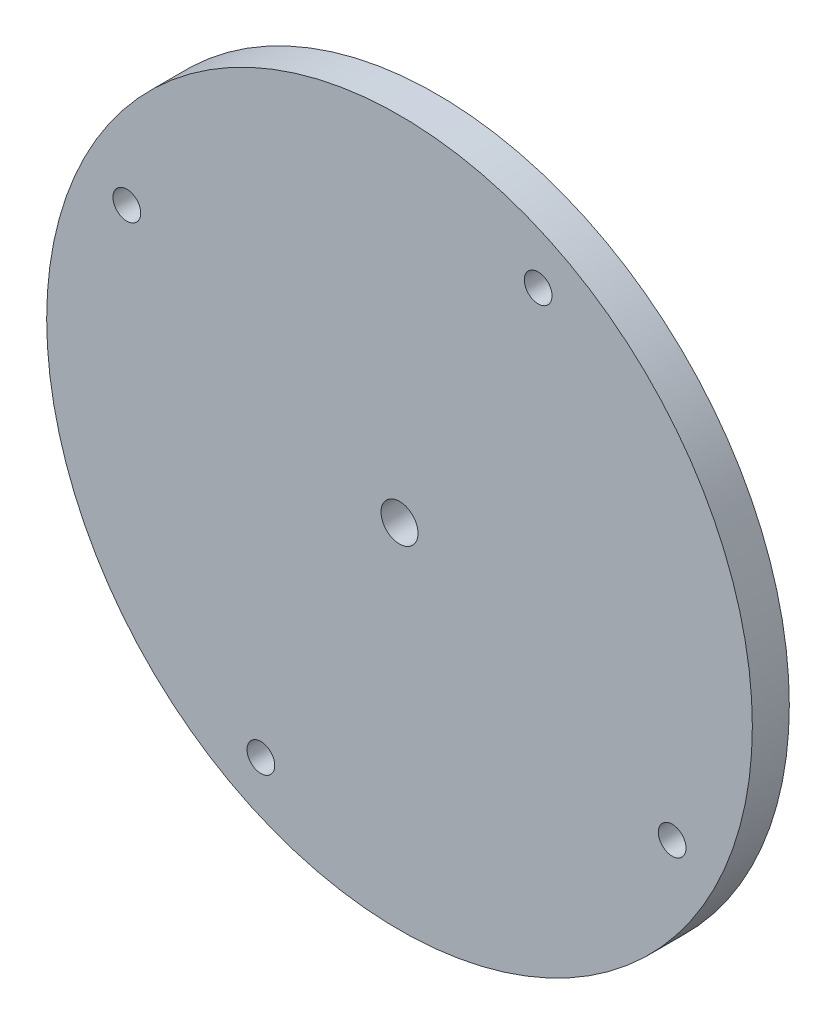
SolidWorks part; units mm, degrees
material "1060 Alloy"
ref_plane "Front Plane" through (0, 0, 0) normal (0, 0, 1) x (1, 0, 0)
ref_plane "Top Plane" through (0, 0, 0) normal (0, 1, 0) x (1, 0, 0)
ref_plane "Right Plane" through (0, 0, 0) normal (1, 0, 0) x (0, 0, -1)
sketch "Sketch1" plane through (0, 0, 0) normal (0, 0, 1) x (1, 0, 0)
  line L5 (50, -50) -> (-50, 50) construction
  line L6 (50, 50) -> (-50, -50) construction
  line L31 (24.5, 59) -> (27.25, 54.2369)
  line L32 (27.25, 54.2369) -> (32.75, 54.2369)
  line L33 (32.75, 54.2369) -> (35.5, 59)
  line L36 (-38.9, 50) -> (38.9, 50) construction
  line L50 (0, -76) -> (0, 122.6166) construction
  line L51 (-76, 0) -> (103.3867, 0) construction
  line L52 (35.5, 59) -> (32.75, 63.7631)
  line L53 (32.75, 63.7631) -> (27.25, 63.7631)
  line L54 (27.25, 63.7631) -> (24.5, 59)
  line L55 (-59, 24.5) -> (-54.2369, 27.25)
  line L56 (-54.2369, 27.25) -> (-54.2369, 32.75)
  line L57 (-54.2369, 32.75) -> (-59, 35.5)
  line L58 (-59, 35.5) -> (-63.7631, 32.75)
  line L59 (-63.7631, 32.75) -> (-63.7631, 27.25)
  line L60 (-63.7631, 27.25) -> (-59, 24.5)
  line L61 (59, -24.5) -> (54.2369, -27.25)
  line L62 (54.2369, -27.25) -> (54.2369, -32.75)
  line L96 (54.2369, -32.75) -> (59, -35.5)
  line L97 (59, -35.5) -> (63.7631, -32.75)
  line L98 (63.7631, -32.75) -> (63.7631, -27.25)
  line L99 (63.7631, -27.25) -> (59, -24.5)
  line L100 (-24.5, -59) -> (-27.25, -54.2369)
  line L101 (-27.25, -54.2369) -> (-32.75, -54.2369)
  line L102 (-32.75, -54.2369) -> (-35.5, -59)
  line L103 (-35.5, -59) -> (-32.75, -63.7631)
  line L104 (-32.75, -63.7631) -> (-27.25, -63.7631)
  line L105 (-27.25, -63.7631) -> (-24.5, -59)
  arc A0 (0, 76.35) -> (-72.3486, -24.3928) centre (0, 0) ccw
  circle A1 centre (30, 59) radius 3
  arc A2 (76.35, 0) -> (0, 76.35) centre (0, 0) ccw
  arc A3 (-72.3486, -24.3928) -> (0, -76.35) centre (0, 0) ccw
  arc A4 (0, -76.35) -> (76.35, 0) centre (0, 0) ccw
  circle A5 centre (59, -30) radius 3
  circle A6 centre (-30, -59) radius 3
  circle A7 centre (-59, 30) radius 3
  circle A8 centre (30, 59) radius 5.5 construction
  circle A9 centre (-59, 30) radius 5.5 construction
  circle A10 centre (59, -30) radius 5.5 construction
  circle A11 centre (-30, -59) radius 5.5 construction
  dimension "D1" = 152.7
  dimension "D9" = 30
  dimension "D2" = 59
  dimension "D15" = 11
  dimension "D16" = 11
  dimension "D17" = 11
  dimension "D3" = 30
  dimension "D4" = 59
  dimension "D5" = 59
  dimension "D6" = 59
  dimension "D10" = 30
  dimension "D11" = 30
extrude "Boss-Extrude3" add sketch "Sketch1" along normal blind 8
sketch "Sketch2" plane through (0, 0, 8) normal (0, 0, 1) x (1, 0, 0)
  circle A0 centre (0, 0) radius 4
  dimension "D1" = 8
extrude "Cut-Extrude1" cut sketch "Sketch2" against normal through all
